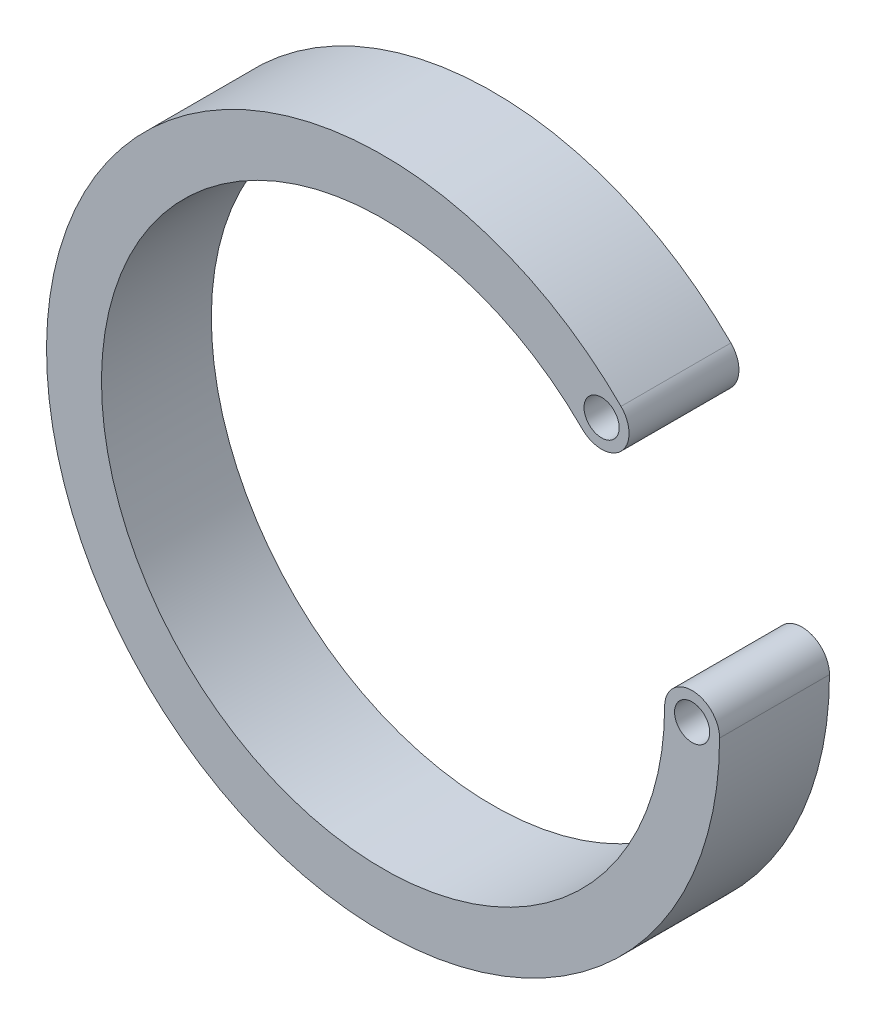
SolidWorks part; units mm, degrees
ref_plane "Front Plane" through (0, 0, 0) normal (0, 0, 1) x (1, 0, 0)
ref_plane "Top Plane" through (0, 0, 0) normal (0, 1, 0) x (1, 0, 0)
ref_plane "Right Plane" through (0, 0, 0) normal (1, 0, 0) x (0, 0, -1)
sketch "Sketch1" plane through (0, 0, 0) normal (0, 0, 1) x (1, 0, 0)
  line L0 (23.0119, 23.0119) -> (27.502, 27.502) construction
  line L1 (32.5437, 0) -> (38.8937, 0) construction
  line L2 (0, 0) -> (32.5437, 0) construction
  arc A0 (23.0119, 23.0119) -> (32.5437, 0) centre (0, 0) ccw
  arc A1 (27.502, 27.502) -> (38.8937, 0) centre (0, 0) ccw
  arc A2 (32.5437, 0) -> (38.8937, 0) centre (35.7187, 0) cw
  arc A3 (27.502, 27.502) -> (23.0119, 23.0119) centre (25.257, 25.257) cw
  circle A4 centre (35.7187, 0) radius 2.032
  circle A5 centre (25.257, 25.257) radius 2.032
  dimension "D1" = 32.5437
  dimension "D2" = 4.064
  dimension "D3" = 38.8937
  dimension "D4" = 45
extrude "Boss-Extrude1" add sketch "Sketch1" along normal blind 12.7 contours A3 A1 A2 A0 A5 A4
equation "\"D3@Sketch1\"=\"D1@Sketch1\"+.25"
